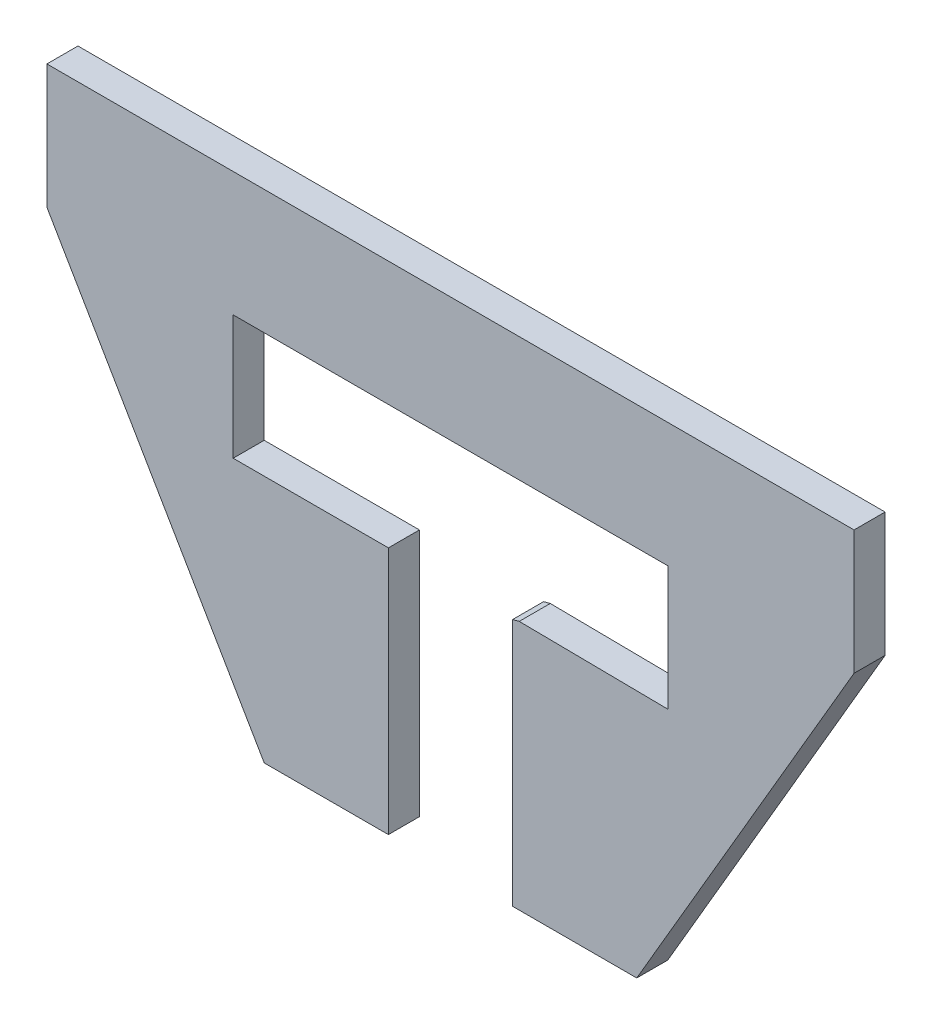
SolidWorks part; units mm, degrees
ref_plane "Front Plane" through (0, 0, 0) normal (0, 0, 1) x (1, 0, 0)
ref_plane "Top Plane" through (0, 0, 0) normal (0, 1, 0) x (1, 0, 0)
ref_plane "Right Plane" through (0, 0, 0) normal (1, 0, 0) x (0, 0, -1)
sketch "Sketch1" plane through (0, 0, 0) normal (0, 0, 1) x (1, 0, 0)
  line L0 (0, 76.2) -> (44.45, 0)
  line L1 (0, 0) -> (165.1, 0)
  line L2 (0, 0) -> (0, 101.6)
  line L3 (0, 101.6) -> (165.1, 101.6)
  line L4 (165.1, 0) -> (165.1, 101.6)
  line L5 (120.65, 0) -> (165.1, 76.2)
  dimension "D1" = 101.6
  dimension "D2" = 165.1
  dimension "D3" = 25.4
  dimension "D4" = 25.4
  dimension "D5" = 44.45
  dimension "D6" = 44.45
extrude "Boss-Extrude1" add sketch "Sketch1" along normal blind 6.35 contours L1 L5 L4 L3 L2 L0
sketch "Sketch2" plane through (0, 0, 6.35) normal (0, 0, 1) x (1, 0, 0)
  line L6 (0, 101.6) -> (165.1, 101.6) construction
  line L7 (38.1, 76.2) -> (127, 76.2)
  line L8 (38.1, 76.2) -> (38.1, 50.8)
  line L10 (127, 76.2) -> (127, 50.8)
  line L11 (44.45, 0) -> (120.65, 0) construction
  line L12 (69.85, 0) -> (95.25, 0)
  line L13 (69.85, 0) -> (69.85, 50.8)
  line L15 (95.25, 0) -> (95.25, 50.8)
  line L16 (0, 76.2) -> (0, 101.6) construction
  line L17 (38.1, 50.8) -> (69.85, 50.8)
  line L18 (95.25, 50.8) -> (96.6132, 51.1563)
  line L19 (96.6132, 51.1563) -> (127, 50.8)
  dimension "D1" = 88.9
  dimension "D2" = 38.1
  dimension "D3" = 25.4
  dimension "D4" = 25.4
  dimension "D5" = 25.4
  dimension "D6" = 69.85
extrude "Cut-Extrude1" cut sketch "Sketch2" against normal blind 6.35
